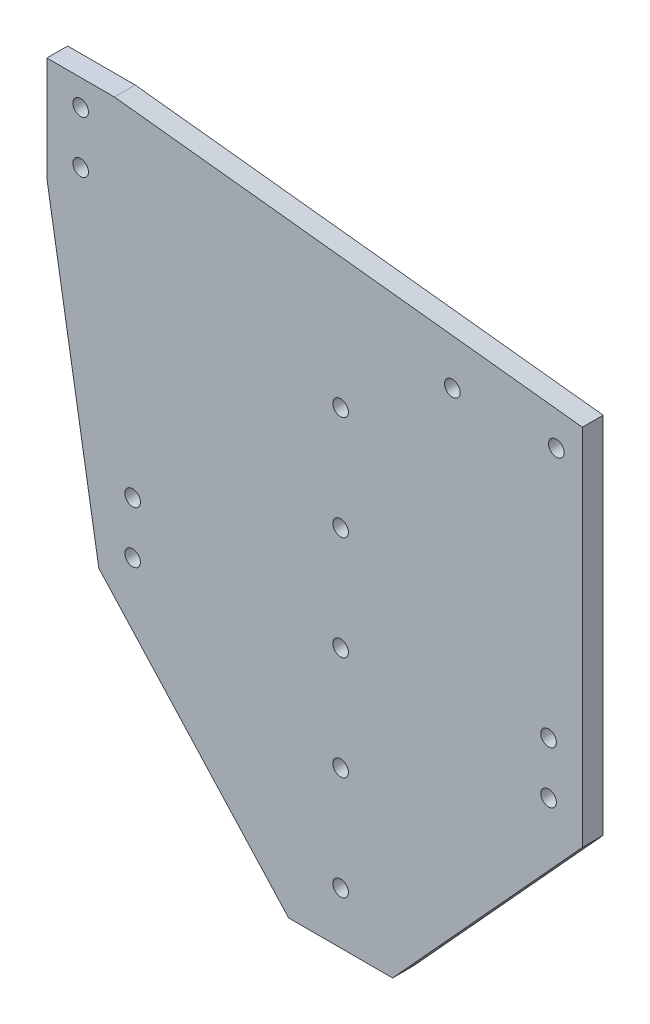
SolidWorks part; units mm, degrees
ref_plane "前视基准面" through (0, 0, 0) normal (0, 0, 1) x (1, 0, 0)
ref_plane "上视基准面" through (0, 0, 0) normal (0, 1, 0) x (1, 0, 0)
ref_plane "右视基准面" through (0, 0, 0) normal (1, 0, 0) x (0, 0, -1)
other "Configuration Table"
sketch "草图1" plane through (0, 0, 0) normal (0, 0, 1) x (1, 0, 0)
  line L0 (0, 0) -> (0, 70)
  line L4 (-46.5, -40) -> (-46.5, 75.1667) construction
  line L5 (-94.6667, 10) -> (-46.5, 10) construction
  line L6 (-86.5, 10) -> (-86.5, 0) construction
  line L7 (-93, 0) -> (-56.5, -40)
  line L8 (-56.5, -40) -> (-36.5, -40)
  line L9 (-36.5, -40) -> (0, 0)
  line L10 (-93, 0) -> (0, 0) construction
  line L11 (-96.5, 75) -> (-96.5, 65) construction
  line L12 (-46.5, 10) -> (-46.5, 30) construction
  line L13 (0, 64) -> (-5, 64) construction
  line L14 (-5, 64) -> (-25, 64) construction
  line L16 (-103, 80) -> (-90, 80)
  line L17 (-90, 80) -> (0, 70)
  line L18 (-103, 80) -> (-103, 60)
  line L19 (-103, 60) -> (-93, 0)
  line L20 (-96.5, 75) -> (-96.5, 80) construction
  circle A0 centre (-86.5, 15) radius 1.5
  circle A1 centre (-86.5, 5) radius 1.5
  circle A2 centre (-6.5, 5) radius 1.5
  circle A3 centre (-6.5, 15) radius 1.5
  circle A4 centre (-96.5, 75) radius 1.5
  circle A5 centre (-96.5, 65) radius 1.5
  circle A6 centre (-46.5, 10) radius 1.5
  circle A7 centre (-46.5, 30) radius 1.5
  circle A8 centre (-46.5, 50) radius 1.5
  circle A9 centre (-46.5, -10) radius 1.5
  circle A10 centre (-46.5, -30) radius 1.5
  circle A11 centre (-5, 64) radius 1.5
  circle A12 centre (-25, 64) radius 1.5
  point P17 (-86.5, 5)
  point P24 (-46.5, -40)
  dimension "D1" = 3
  dimension "D3" = 6.5
  dimension "D4" = 80
  dimension "D10" = 3
  dimension "D12" = 93
  dimension "D13" = 3
  dimension "D17" = 20
  dimension "D21" = 3
  dimension "D2" = 20
  dimension "D5" = 70
  dimension "D6" = 10
  dimension "D7" = 40
  dimension "D9" = 10
  dimension "D11" = 50
  dimension "D15" = 20
  dimension "D18" = 5
  dimension "D19" = 6
  dimension "D20" = 20
  dimension "D22" = 13
  dimension "D23" = 80
  dimension "D24" = 5
  dimension "D25" = 20
  dimension "D8" = 2
  dimension "D14" = 3
  dimension "D16" = 3
extrude "凸台-拉伸1" add sketch "草图1" along normal blind 4
